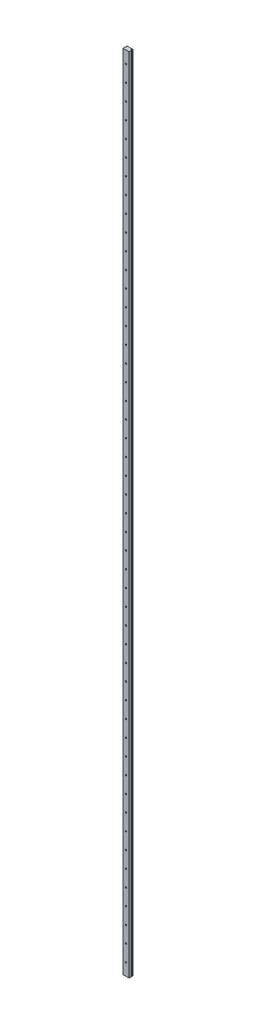
SolidWorks part; units mm, degrees
material "Plain Carbon Steel"
ref_plane "Front" through (0, 0, 0) normal (0, 0, 1) x (1, 0, 0)
ref_plane "Top" through (0, 0, 0) normal (0, 1, 0) x (1, 0, 0)
ref_plane "Right" through (0, 0, 0) normal (1, 0, 0) x (0, 0, -1)
sketch "Sketch1" plane through (0, 0, 0) normal (0, 1, 0) x (1, 0, 0)
  line L0 (-5.5, 2) -> (5.5, 2) construction
  line L1 (7.5, -5) -> (-7.5, -5)
  line L2 (7.5, -5) -> (7.5, 0.75)
  line L3 (7.5, 5) -> (-7.5, 5)
  line L4 (-7.5, -5) -> (-7.5, 0.75)
  line L5 (7.5, -5) -> (-7.5, 5) construction
  line L6 (7.5, 5) -> (-7.5, -5) construction
  line L7 (-7.5, 2) -> (-5.5, 2) construction
  line L8 (-6.3544, 2.5) -> (-5.5, 2.5)
  line L10 (-6.3544, 1.5) -> (-5.5, 1.5)
  line L11 (-5.5, 2.5) -> (-5.5, 1.5)
  line L12 (6.3544, 2.5) -> (5.5, 2.5)
  line L14 (6.3544, 1.5) -> (5.5, 1.5)
  line L15 (5.5, 2.5) -> (5.5, 1.5)
  line L16 (5.5, 2) -> (7.5, 2) construction
  line L17 (7.5, 3.25) -> (7.5, 5)
  line L18 (-7.5, 3.25) -> (-7.5, 5)
  line L19 (-7.5, 3.25) -> (-7.5, 0.75) construction
  line L20 (7.5, 3.25) -> (7.5, 0.75) construction
  arc A0 (-6.3544, 2.5) -> (-7.5, 3.25) centre (-7.5, 2) ccw
  arc A1 (6.3544, 1.5) -> (7.5, 0.75) centre (7.5, 2) ccw
  arc A2 (-7.5, 0.75) -> (-6.3544, 1.5) centre (-7.5, 2) ccw
  arc A3 (7.5, 3.25) -> (6.3544, 2.5) centre (7.5, 2) ccw
  point P0 (0, 0)
  dimension "D3" = 2.5
  dimension "D4" = 2.5
  dimension "D1" = 15
  dimension "D2" = 10
  dimension "D5" = 3
  dimension "D6" = 2
  dimension "D7" = 1
extrude "Boss-Extrude1" add sketch "Sketch1" along normal mid plane 1980
chamfer "Chamfer1" distance 0.5 angle 45 4 edges at (-7.5, 0, 5) (-7.5, 0, -5) (7.5, 0, 5) (7.5, 0, -5)
hole_wizard "CBORE for M3 Hex Socket Head Cap Screw1" positions "Sketch2" profile "Sketch4" counterbore size "M3" standard "DIN" end condition up to next
sketch "Sketch2" plane through (0, 0, -5) normal (0, 0, -1) x (-1, 0, 0)
  point P0 (0, 0)
sketch "Sketch4" plane through (0, 0, -5) normal (1, 0, 0) x (0, 1, 0)
  line L0 (0, 0) -> (0, 10)
  line L1 (0, 10) -> (1.7, 10)
  line L3 (1.7, 10) -> (1.7, 3.9)
  line L4 (3.25, 3.9) -> (1.7, 3.9)
  line L5 (3.25, 3.9) -> (3.25, 0.5)
  line L6 (3.25, 0.5) -> (3.75, 0)
  line L7 (3.75, 0) -> (0, 0)
  line L8 (-3.25, 0.5) -> (-3.75, 0) construction
  line L11 (0, -6.35) -> (0, 107.95) construction
  dimension "Thru Hole Dia." = 3.4
  dimension "Thru Hole Depth" = 10
  dimension "C'Bore Dia." = 6.5
  dimension "C'Bore Depth" = 3.9
  dimension "Near C'Sink Dia." = 7.5
  dimension "Near C'Sink Angle" = 90
pattern_linear "LPattern1" count 25 spacing 40 along (0, -1, 0) count 25 spacing 40 along (0, 1, 0) of "CBORE for M3 Hex Socket Head Cap Screw1"
